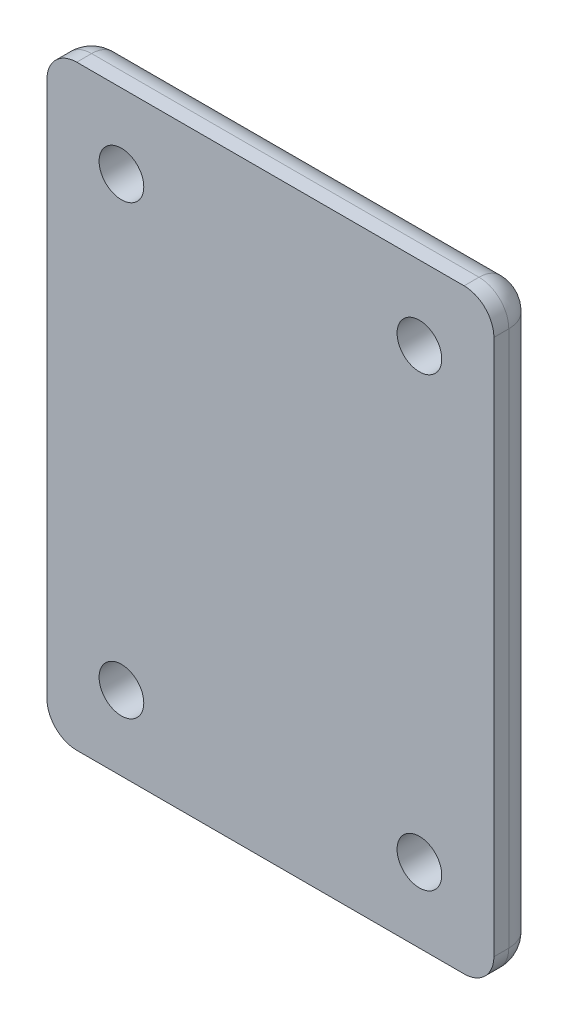
SolidWorks part; units mm, degrees
ref_plane "前视基准面" through (0, 0, 0) normal (0, 0, 1) x (1, 0, 0)
ref_plane "上视基准面" through (0, 0, 0) normal (0, 1, 0) x (1, 0, 0)
ref_plane "右视基准面" through (0, 0, 0) normal (1, 0, 0) x (0, 0, -1)
sketch "草图1" plane through (0, 0, 0) normal (0, 0, 1) x (1, 0, 0)
  line L1 (-15, 20) -> (15, 20)
  line L2 (-15, 20) -> (-15, -20)
  line L3 (-15, -20) -> (15, -20)
  line L4 (15, 20) -> (15, -20)
  line L5 (-15, 20) -> (15, -20) construction
  line L6 (-15, -20) -> (15, 20) construction
  point P0 (0, 0)
  dimension "D1" = 30
  dimension "D2" = 40
extrude "凸台-拉伸1" add sketch "草图1" along normal blind 3
sketch "草图2" plane through (0, 0, 3) normal (0, 0, 1) x (1, 0, 0)
  line L0 (15, 20) -> (-15, 20) construction
  line L1 (-15, 20) -> (-15, -20) construction
  line L2 (15, -20) -> (15, 20) construction
  line L3 (-15, -20) -> (15, -20) construction
  circle A0 centre (10, 15) radius 1.5
  circle A1 centre (-10, 15) radius 1.5
  circle A2 centre (10, -15) radius 1.5
  circle A3 centre (-10, -15) radius 1.5
  dimension "D1" = 5
  dimension "D2" = 5
  dimension "D3" = 5
  dimension "D4" = 5
  dimension "D5" = 5
  dimension "D6" = 5
  dimension "D7" = 5
  dimension "D8" = 5
extrude "切除-拉伸1" cut sketch "草图2" against normal blind 10
fillet "圆角1" radius 2 8 edges at (15, 0, 0) (15, -20, 1.5) (0, -20, 0) (-15, -20, 1.5) (-15, 0, 0) (0, 20, 0) (15, 20, 1.5) (-15, 20, 1.5)
